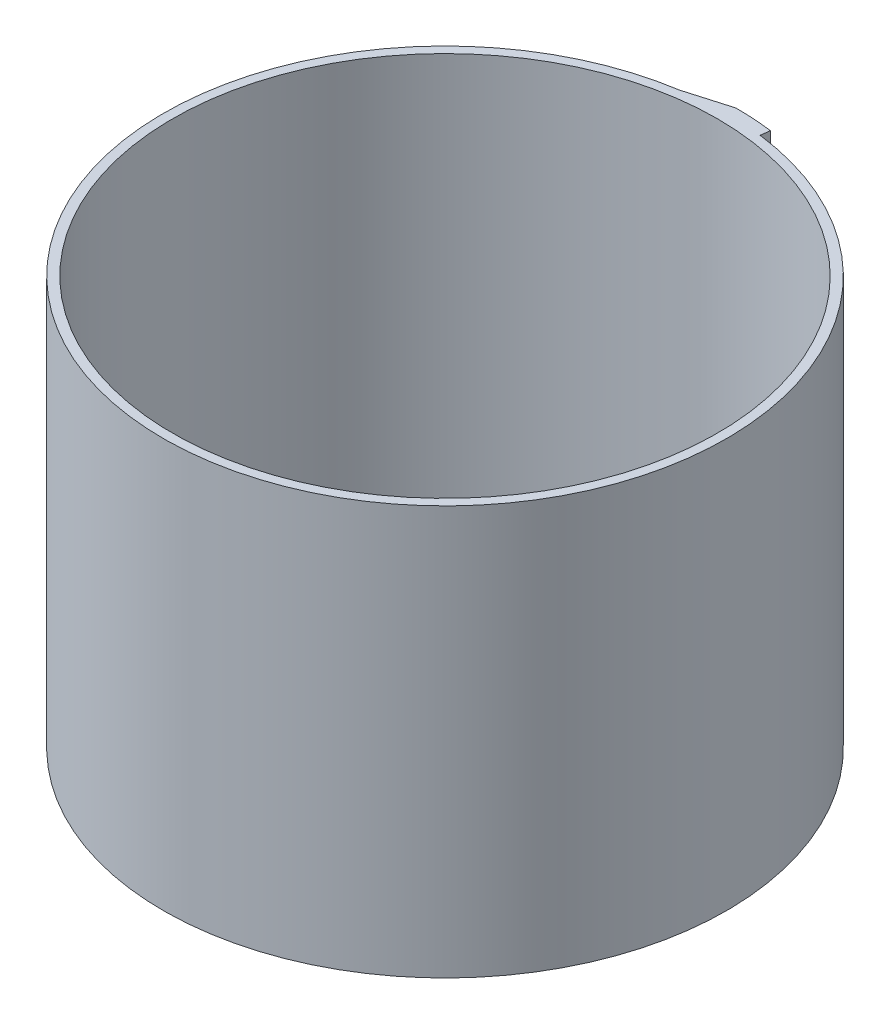
SolidWorks part; units mm, degrees
material "Brass"
ref_plane "Front Plane" through (0, 0, 0) normal (0, 0, 1) x (1, 0, 0)
ref_plane "Top Plane" through (0, 0, 0) normal (0, 1, 0) x (1, 0, 0)
ref_plane "Right Plane" through (0, 0, 0) normal (1, 0, 0) x (0, 0, -1)
sketch "Sketch1" plane through (0, 0, 0) normal (0, 1, 0) x (1, 0, 0)
  line L0 (0, 31) -> (0, 32.02)
  line L1 (4.0647, 31.761) -> (3.9353, 30.7492)
  line L2 (0, 32.02) -> (-4.8017, 30.6259)
  circle A0 centre (0, 0) radius 29.98
  circle A1 centre (0, 0) radius 31
  arc A2 (0, 32.02) -> (4.0647, 31.761) centre (0, 0) cw
  point P11 (4, 31.2551)
  dimension "D2" = 62
  dimension "D1" = 1.02
  dimension "D3" = 1.02
  dimension "D4" = 4
  dimension "D5" = 5
extrude "Boss-Extrude1" add sketch "Sketch1" along normal blind 45 contours A2 L0 A1 L1 | A1 L0 L2 | A1 A0
equation "\"D3@Sketch1\"=\"D1@Sketch1\""
